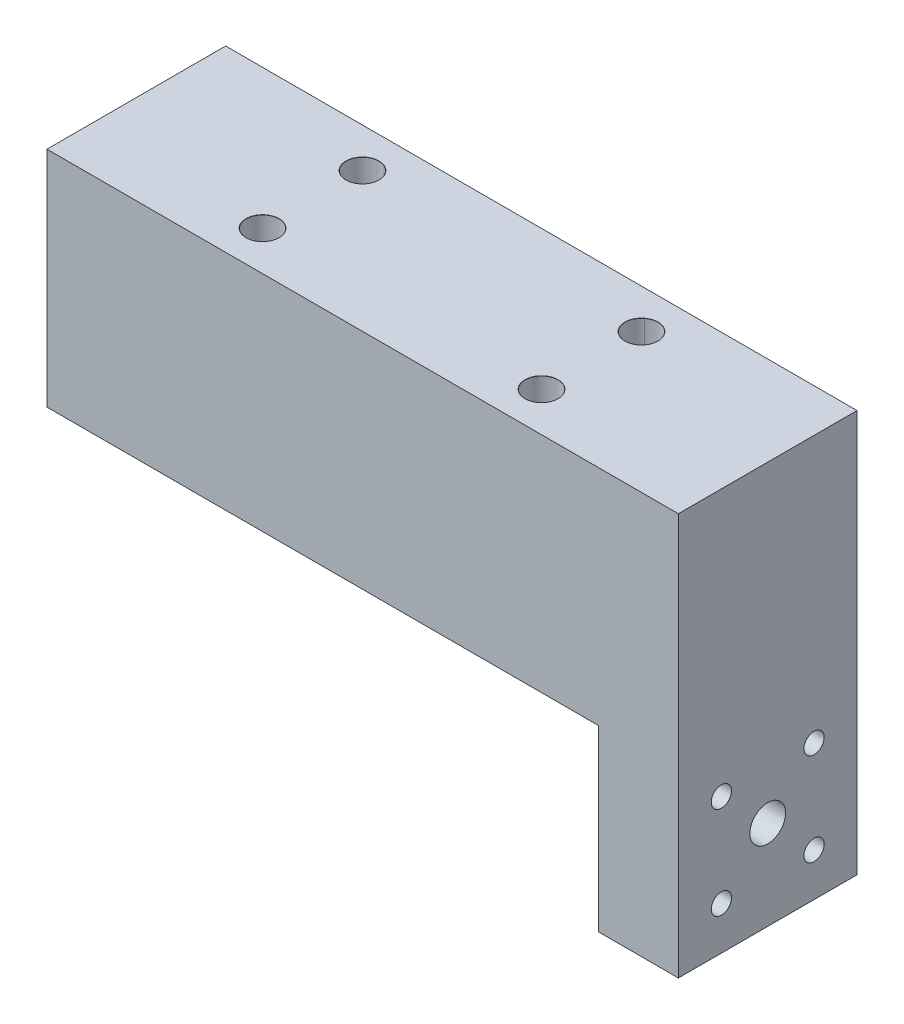
SolidWorks part; units mm, degrees
ref_plane "Front Plane" through (0, 0, 0) normal (0, 0, 1) x (1, 0, 0)
ref_plane "Top Plane" through (0, 0, 0) normal (0, 1, 0) x (1, 0, 0)
ref_plane "Right Plane" through (0, 0, 0) normal (1, 0, 0) x (0, 0, -1)
sketch "Sketch1" plane through (0, 0, 0) normal (0, 0, 1) x (1, 0, 0)
  line L1 (-60.206, 27.9097) -> (45.794, 27.9097)
  line L2 (-60.206, 27.9097) -> (-60.206, -39.5903)
  line L3 (-60.206, -39.5903) -> (45.794, -39.5903)
  line L4 (45.794, 27.9097) -> (45.794, -39.5903)
  dimension "D1" = 106
  dimension "D2" = 67.5
extrude "Boss-Extrude1" add sketch "Sketch1" along normal blind 30
sketch "Sketch2" plane through (0, 0, 0) normal (0, 0, 1) x (1, 0, 0)
  line L1 (-60.206, -39.5903) -> (32.394, -39.5903)
  line L2 (-60.206, -39.5903) -> (-60.206, -9.5903)
  line L3 (-60.206, -9.5903) -> (32.394, -9.5903)
  line L4 (32.394, -39.5903) -> (32.394, -9.5903)
  dimension "D1" = 30
  dimension "D2" = 92.6
extrude "Boss-Extrude2" add sketch "Sketch2" along normal blind 30
sketch "Sketch3" plane through (0, 0, 0) normal (0, 0, 1) x (1, 0, 0)
  line L1 (-60.206, -39.5903) -> (32.394, -39.5903)
  line L2 (-60.206, -39.5903) -> (-60.206, -9.5903)
  line L3 (-60.206, -9.5903) -> (32.394, -9.5903)
  line L4 (32.394, -39.5903) -> (32.394, -9.5903)
  dimension "D1" = 92.6
  dimension "D2" = 30
extrude "Cut-Extrude1" cut sketch "Sketch3" along normal blind 30
sketch "Sketch4" plane through (45.794, 0, 0) normal (1, 0, 0) x (0, 0, -1)
  circle A0 centre (-15, -24.5903) radius 3
  dimension "D1" = 6
extrude "Cut-Extrude2" cut sketch "Sketch4" against normal blind 30
hole_wizard "M3 Clearance Hole1" positions "Sketch9" profile "Sketch10" hole size "M3" standard "ISO" end condition through all
sketch "Sketch9" plane through (32.394, 0, 0) normal (-1, 0, 0) x (0, 0, 1)
  line L0 (0, -9.5903) -> (30, -39.5903) construction
  line L1 (30, -39.5903) -> (0, -39.5903) construction
  line L2 (30, -39.5903) -> (30, -9.5903) construction
  line L4 (30, -9.5903) -> (0, -39.5903) construction
  circle A0 centre (15, -24.5903) radius 11 construction
  point P17 (7.2218, -16.8121)
  point P19 (22.7782, -16.8121)
  point P21 (22.7782, -32.3685)
  point P23 (7.2218, -32.3685)
  dimension "D1" = 22
sketch "Sketch10" plane through (32.394, -32.3685, 7.2218) normal (0, 1, 0) x (0, 0, 1)
  line L0 (0, 0) -> (0, 13.4)
  line L1 (0, 13.4) -> (1.7, 13.4)
  line L2 (1.7, 13.4) -> (1.7, 0.025)
  line L3 (1.7, 0.025) -> (1.725, 0)
  line L5 (1.725, 0) -> (0, 0)
  line L6 (-1.7, 0.025) -> (-1.725, 0) construction
  line L11 (0, -6.35) -> (0, 107.95) construction
  dimension "Thru Hole Dia." = 3.4
  dimension "Thru Hole Depth" = 13.4
  dimension "Near C'Sink Dia." = 3.45
  dimension "Near C'Sink Angle" = 90
sketch "Sketch11" plane through (32.394, 0, 0) normal (-1, 0, 0) x (0, 0, 1)
  circle A0 centre (15, -24.5903) radius 9
  dimension "D1" = 18
extrude "Cut-Extrude3" cut sketch "Sketch11" against normal blind 2
hole_wizard "M5 Clearance Hole1" positions "3DSketch2" profile "Sketch12" hole size "M5" standard "ISO"
sketch3d "3DSketch2"
  point P10 (16.2122, 27.9097, 6.6142)
  point P213 (-30.6242, 27.9097, 23.3858)
  point P214 (16.2122, 27.9097, 23.3858)
  point P215 (-30.6242, 27.9097, 6.6142)
  point P225 (-30.6242, 27.9097, 6.6142)
  point P229 (-30.6242, 27.9097, 6.6142)
  point P230 (16.2122, 27.9097, 6.6142)
  point P232 (16.2122, 27.9097, 23.3858)
  point P233 (-30.6242, 27.9097, 23.3858)
  point P247 (-30.6242, 27.9097, 6.6142)
  point P248 (-30.6242, 27.9097, 6.6142)
  point P250 (-30.6242, 27.9097, 6.6142)
  point P251 (-30.6242, 27.9097, 6.6142)
  point P260 (16.2122, 27.9097, 6.6142)
  point P262 (-30.6242, 27.9097, 6.6142)
  point P263 (-30.6242, 27.9097, 6.6142)
  point P265 (-30.6242, 27.9097, 6.6142)
  point P267 (16.2122, 27.9097, 6.6142)
  point P269 (16.2122, 27.9097, 6.6142)
  point P271 (16.2122, 27.9097, 23.3858)
  point P272 (-30.6242, 27.9097, 23.3858)
sketch "Sketch12" plane through (-30.6242, 27.9097, 23.3858) normal (1, 0, 0) x (0, 0, 1)
  line L0 (0, 0) -> (0, 67.5)
  line L1 (0, 67.5) -> (2.75, 67.5)
  line L2 (2.75, 67.5) -> (2.75, 0.025)
  line L3 (2.75, 0.025) -> (2.775, 0)
  line L5 (2.775, 0) -> (0, 0)
  line L6 (-2.75, 0.025) -> (-2.775, 0) construction
  line L11 (0, -6.35) -> (0, 107.95) construction
  dimension "Thru Hole Dia." = 5.5
  dimension "Thru Hole Depth" = 67.5
  dimension "Near C'Sink Dia." = 5.55
  dimension "Near C'Sink Angle" = 90
equation "\"L1\"= 30mm"
equation "\"L2\"= 92.6mm"
equation "\"Base\"= 30mm"
equation "\"WallHeight\"= 37.5mm"
equation "\"MotorRecessDia\"= 18mm"
equation "\"BoltCircle\"= 22mm"
equation "\"MotorRecessDepth\"= 2mm"
equation "\"D1@Sketch9\"=\"BoltCircle\""
equation "\"ShaftDia\"= 6mm"
equation "\"D1@Cut-Extrude3\"=\"MotorRecessDepth\""
equation "\"D1@Cut-Extrude2\"=\"L1\""
equation "\"D1@Boss-Extrude1\"=\"Base\""
equation "\"D1@Boss-Extrude2\"=\"L1\""
equation "\"D1@Cut-Extrude1\"=\"Base\""
equation "\"D1@Sketch4\"=\"ShaftDia\""
equation "\"D1@Sketch11\"=\"MotorRecessDia\""
equation "\"TotalY\"= 67.5mm"
equation "\"TotalX\"= 106mm"
equation "\"D1@Sketch1\"=\"TotalX\""
equation "\"D2@Sketch1\"=\"TotalY\""
equation "\"D2@Sketch2\"=\"L2\""
equation "\"D1@Sketch2\"=\"Base\""
equation "\"D1@Sketch3\"=\"L2\""
equation "\"D2@Sketch3\"=\"L1\""
equation "\"MotorHeight\"= 13.4mm"
equation "\"Thru Hole Depth@Sketch10\"=\"MotorHeight\""
